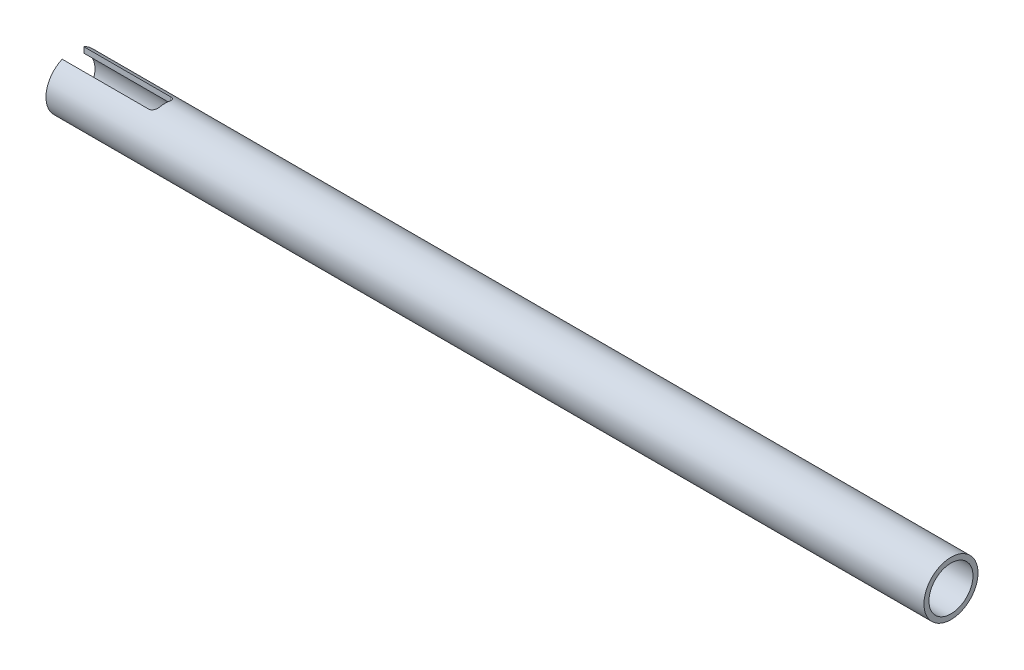
SolidWorks part; units mm, degrees
material "AISI 4130 Steel, annealed at 865C"
ref_plane "X-Y Datum" through (0, 0, 0) normal (0, 0, 1) x (1, 0, 0)
ref_plane "X-Z Datum" through (0, 0, 0) normal (0, 1, 0) x (1, 0, 0)
ref_plane "Y-Z Datum" through (0, 0, 0) normal (1, 0, 0) x (0, 0, -1)
sketch "Sketch1" plane through (0, 0, 0) normal (1, 0, 0) x (0, 0, -1)
  circle A0 centre (0, 0) radius 6.4643
  circle A1 centre (0, 0) radius 7.9375
  dimension "D1" = 15.875
  dimension "D2" = 12.9286
extrude "Boss-Extrude1" add sketch "Sketch1" against normal offset from surface 25.4 and the other way up to surface (153.62 mm away) contours A1
ref_plane "Plane1" through (0, 7.9375, 0) normal (0, 1, 0) x (1, 0, 0)
sketch "Sketch2" plane through (0, 7.9375, 0) normal (0, 1, 0) x (1, 0, 0)
  line L0 (-80.4032, 3.175) -> (-112.4707, 3.175) construction
  line L1 (-80.4032, 3.175) -> (-112.4707, 3.175)
  line L3 (-80.4032, -3.175) -> (-78.8157, -3.175) construction
  line L4 (-78.8157, 3.175) -> (-80.4032, 3.175) construction
  line L5 (-112.4707, -3.175) -> (-80.4032, -3.175) construction
  line L7 (-80.4032, -3.175) -> (-78.8157, -3.175)
  line L8 (-78.8157, 3.175) -> (-80.4032, 3.175)
  line L9 (-112.4707, -3.175) -> (-80.4032, -3.175)
  line L10 (-78.8157, 3.175) -> (-77.2282, 3.175)
  line L11 (-77.2282, 3.175) -> (-77.2282, -3.175)
  line L12 (-77.2282, -3.175) -> (-78.8157, -3.175)
  line L13 (-112.4707, -3.175) -> (-112.4707, 3.175)
  dimension "D1" = 1.5875
extrude "Cut-Extrude1" cut sketch "Sketch2" against normal through all contours L1 L13 L9 L7 L12 L11 L10 L8
fillet "Fillet1" radius 1.5875 4 edges at (-77.2282, -6.4528, -3.175) (-77.2282, 6.4528, -3.175) (-77.2282, -6.4528, 3.175) (-77.2282, 6.4528, 3.175)
